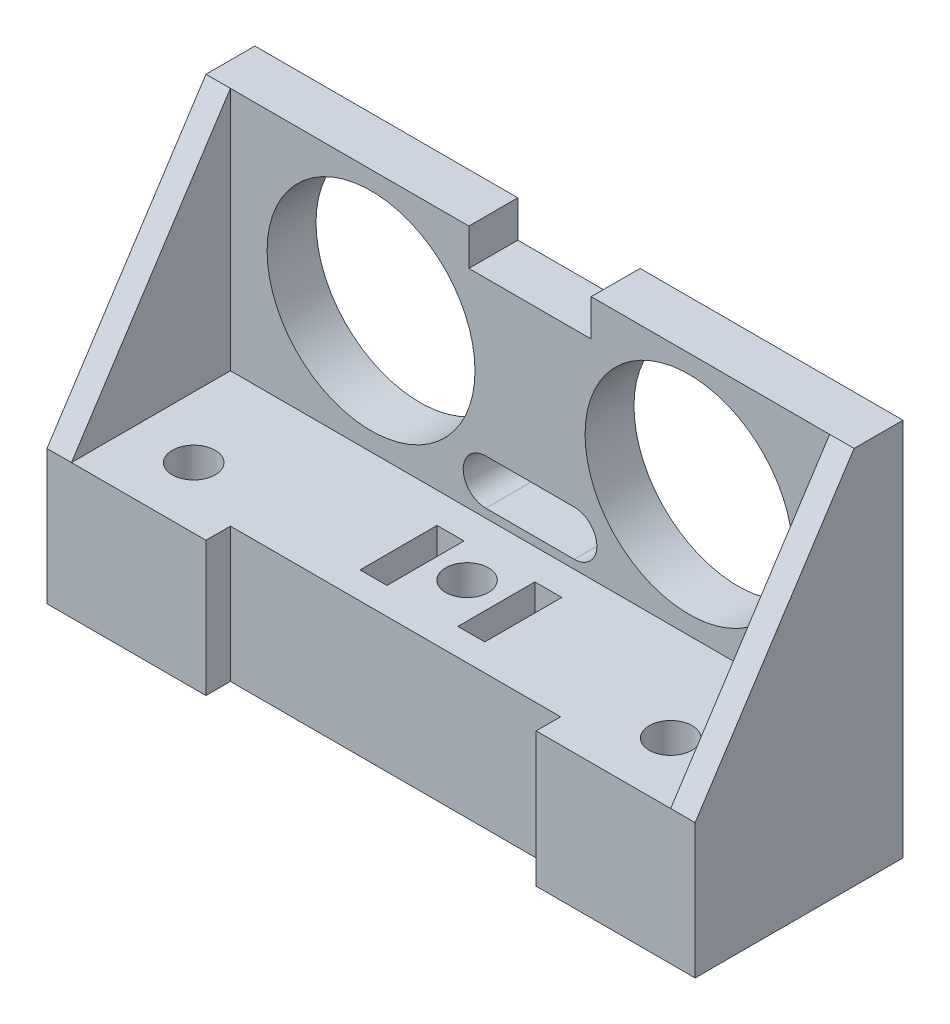
SolidWorks part; units mm, degrees
ref_plane "Front Plane" through (0, 0, 0) normal (0, 0, 1) x (1, 0, 0)
ref_plane "Top Plane" through (0, 0, 0) normal (0, 1, 0) x (1, 0, 0)
ref_plane "Right Plane" through (0, 0, 0) normal (1, 0, 0) x (0, 0, -1)
sketch "Sketch1" plane through (0, 0, 0) normal (0, 0, 1) x (1, 0, 0)
  line L3 (-10.4195, -6.2931) -> (38.5805, -6.2931)
  line L8 (-10.4195, 18.7069) -> (-10.4195, -6.2931)
  line L9 (10.4655, 3.1169) -> (17.6955, 3.1169)
  line L12 (10.4655, -0.5831) -> (17.6955, -0.5831)
  line L16 (14.0805, 15.7069) -> (19.0805, 15.7069)
  line L18 (19.0805, 15.7069) -> (19.0805, 18.7069)
  line L19 (14.0805, 15.7069) -> (9.0805, 15.7069)
  line L20 (9.0805, 15.7069) -> (9.0805, 18.7069)
  line L21 (9.0805, 18.7069) -> (19.0805, 18.7069)
  line L28 (38.5805, 18.7069) -> (38.5805, -6.2931)
  line L29 (-10.4195, 18.7069) -> (38.5805, 18.7069)
  circle A0 centre (27.0805, 8.7069) radius 8.5
  circle A1 centre (1.0805, 8.7069) radius 8.5
  arc A6 (10.4655, 3.1169) -> (10.4655, -0.5831) centre (10.4655, 1.2669) ccw
  arc A7 (17.6955, -0.5831) -> (17.6955, 3.1169) centre (17.6955, 1.2669) ccw
  point P22 (14.0805, 3.1169)
  point P31 (-31.9195, 3.1169)
  point P38 (60.0805, 3.1169)
  dimension "D5" = 17
  dimension "D7" = 17
  dimension "D11" = 10
  dimension "D10" = 10
  dimension "D3" = 49
  dimension "D4" = 25
  dimension "D6" = 7.56
  dimension "D8" = 20.885
  dimension "D16" = 7.23
  dimension "D17" = 3.7
  dimension "D22" = 5
  dimension "D23" = 5
extrude "Boss-Extrude1" add sketch "Sketch1" along normal blind 4
sketch "Sketch2" plane through (0, 0, 4) normal (0, 0, 1) x (1, 0, 0)
  line L2 (14.0805, -1.2931) -> (38.5805, -1.2931)
  line L3 (38.5805, 18.7069) -> (38.5805, -6.2931) construction
  line L4 (38.5805, -1.2931) -> (38.5805, -6.2931)
  line L5 (38.5805, -6.2931) -> (-10.4195, -6.2931)
  line L6 (-10.4195, -6.2931) -> (-10.4195, -1.2931)
  line L7 (-10.4195, 18.7069) -> (-10.4195, -6.2931) construction
  line L8 (-10.4195, -1.2931) -> (14.0805, -1.2931)
  dimension "D1" = 5
extrude "Boss-Extrude2" add sketch "Sketch2" along normal blind 13
sketch "Sketch3" plane through (0, -1.2931, 0) normal (0, 1, 0) x (1, 0, 0)
  line L0 (14.0805, 0) -> (14.0805, -17) construction
  line L1 (9.0805, 0) -> (19.0805, 0) construction
  line L2 (38.5805, -17) -> (-10.4195, -17) construction
  line L3 (-10.4195, -4) -> (9.0805, -4) construction
  line L4 (8.9805, -6.5) -> (11.1805, -6.5)
  line L5 (8.9805, -6.5) -> (8.9805, -12.8)
  line L6 (8.9805, -12.8) -> (11.1805, -12.8)
  line L7 (11.1805, -6.5) -> (11.1805, -12.8)
  line L8 (8.9805, -6.5) -> (11.1805, -12.8) construction
  line L9 (8.9805, -12.8) -> (11.1805, -6.5) construction
  line L10 (19.1805, -12.8) -> (16.9805, -6.5) construction
  line L11 (19.1805, -6.5) -> (16.9805, -12.8) construction
  line L12 (16.9805, -6.5) -> (16.9805, -12.8)
  line L13 (19.1805, -12.8) -> (16.9805, -12.8)
  line L14 (19.1805, -6.5) -> (19.1805, -12.8)
  line L15 (19.1805, -6.5) -> (16.9805, -6.5)
  point P6 (10.0805, -9.65)
  point P17 (18.0805, -9.65)
  dimension "D1" = 2.5
  dimension "D2" = 2.2
  dimension "D3" = 6.3
  dimension "D4" = 5.1
extrude "Cut-Extrude1" cut sketch "Sketch3" against normal blind 3.5
sketch "Sketch4" plane through (0, -1.2931, 0) normal (0, 1, 0) x (1, 0, 0)
  line L0 (14.0805, 0) -> (14.0805, -17) construction
  line L1 (9.0805, 0) -> (19.0805, 0) construction
  line L2 (38.5805, -17) -> (-10.4195, -17) construction
  line L3 (9.0805, -4) -> (19.0805, -4) construction
  line L4 (38.5805, -17) -> (38.5805, -4) construction
  circle A0 centre (14.0805, -9.15) radius 1.75
  circle A1 centre (33.5805, -12) radius 1.75
  circle A2 centre (-5.4195, -12) radius 1.75
  dimension "D1" = 3.5
  dimension "D3" = 3.5
  dimension "D4" = 5
  dimension "D5" = 5
  dimension "D2" = 5.15
extrude "Cut-Extrude2" cut sketch "Sketch4" against normal through all
sketch "Sketch6" plane through (0, -1.2931, 0) normal (0, 1, 0) x (1, 0, 0)
  line L0 (14.0805, -17) -> (14.0805, 0) construction
  line L1 (38.5805, -17) -> (-10.4195, -17) construction
  line L2 (9.0805, 0) -> (19.0805, 0) construction
  line L3 (27.5805, -17) -> (0.5805, -17)
  line L4 (0.5805, -17) -> (0.5805, -15)
  line L5 (0.5805, -15) -> (27.5805, -15)
  line L6 (14.0805, -15) -> (14.0805, -17)
  line L7 (27.5805, -17) -> (27.5805, -15)
  line M20 (-10.4195, -17) -> (38.5805, -17)
  dimension "D1" = 2
  dimension "D2" = 13.5
extrude "Cut-Extrude4" cut sketch "Sketch6" against normal through all contours L6 L5 L4 M20 | L3 L7 L5 L6
sketch "Sketch7" plane through (0, 0, 0) normal (0, 0, -1) x (-1, 0, 0)
  line L0 (-38.5805, 18.7069) -> (-40.5805, 18.7069)
  line L1 (-40.5805, 18.7069) -> (-40.5805, -6.2931)
  line L2 (-40.5805, -6.2931) -> (-38.5805, -6.2931)
  line L3 (-38.5805, -6.2931) -> (-38.5805, 18.7069)
  line L4 (-14.0805, -6.2931) -> (-14.0805, 15.7069)
  line L5 (10.4195, -6.2931) -> (-38.5805, -6.2931) construction
  line L6 (-9.0805, 15.7069) -> (-19.0805, 15.7069) construction
  line L7 (10.4195, -6.2931) -> (10.4195, 18.7069)
  line L8 (12.4195, -6.2931) -> (10.4195, -6.2931)
  line L9 (12.4195, 18.7069) -> (12.4195, -6.2931)
  line L10 (10.4195, 18.7069) -> (12.4195, 18.7069)
  dimension "D1" = 90
  dimension "D2" = 2
extrude "Boss-Extrude3" add sketch "Sketch7" against normal blind 17 contours L3 L0 L1 L2 | L7 L10 L9 L8
sketch "Sketch8" plane through (40.5805, 0, 0) normal (1, 0, 0) x (0, 0, -1)
  line L0 (0, 18.7069) -> (-4, 18.7069)
  line L3 (-17, 18.7069) -> (-17, -6.2931) construction
  line L6 (-4, 18.7069) -> (-17, -1.2931)
  line L7 (-4, 18.7069) -> (-17, 18.7069)
  line L8 (-17, 18.7069) -> (-17, -1.2931)
extrude "Cut-Extrude5" cut sketch "Sketch8" against normal blind 72 contours L6 L8 L7
sketch "Sketch9" plane through (0, -6.2931, 0) normal (0, -1, 0) x (-1, 0, 0)
  line L0 (-40.5805, 0) -> (-40.5805, -17)
  line L1 (-40.5805, -17) -> (-27.5805, -17)
  line L2 (-27.5805, -15) -> (-0.5805, -15)
  line L3 (-0.5805, -15) -> (-0.5805, -17)
  line L4 (-0.5805, -17) -> (12.4195, -17)
  line L5 (12.4195, -17) -> (12.4195, 0)
  line L6 (12.4195, 0) -> (-40.5805, 0)
  line L15 (-0.5805, -15) -> (-0.5805, -17)
  line L16 (-0.5805, -17) -> (12.4195, -17)
  line L17 (12.4195, -17) -> (12.4195, 0)
  line L18 (12.4195, 0) -> (-40.5805, 0)
  line L19 (-40.5805, 0) -> (-40.5805, -17)
  line L20 (-40.5805, -17) -> (-27.5805, -17)
  line L21 (-27.5805, -17) -> (-27.5805, -15)
  line L22 (-27.5805, -15) -> (-0.5805, -15)
  line L29 (-27.5805, -17) -> (-27.5805, -15)
  circle A0 centre (5.4195, -12) radius 1.75
  circle A1 centre (-14.0805, -9.15) radius 1.75
  circle A2 centre (-33.5805, -12) radius 1.75
  dimension "D1" = 0
extrude "Boss-Extrude4" add sketch "Sketch9" along normal blind 6
sketch "Sketch10" plane through (0, -12.2931, 0) normal (0, -1, 0) x (-1, 0, 0)
  circle A0 centre (-14.0805, -9.15) radius 2.85
  dimension "D1" = 5.7
extrude "Cut-Extrude6" cut sketch "Sketch10" against normal blind 8
